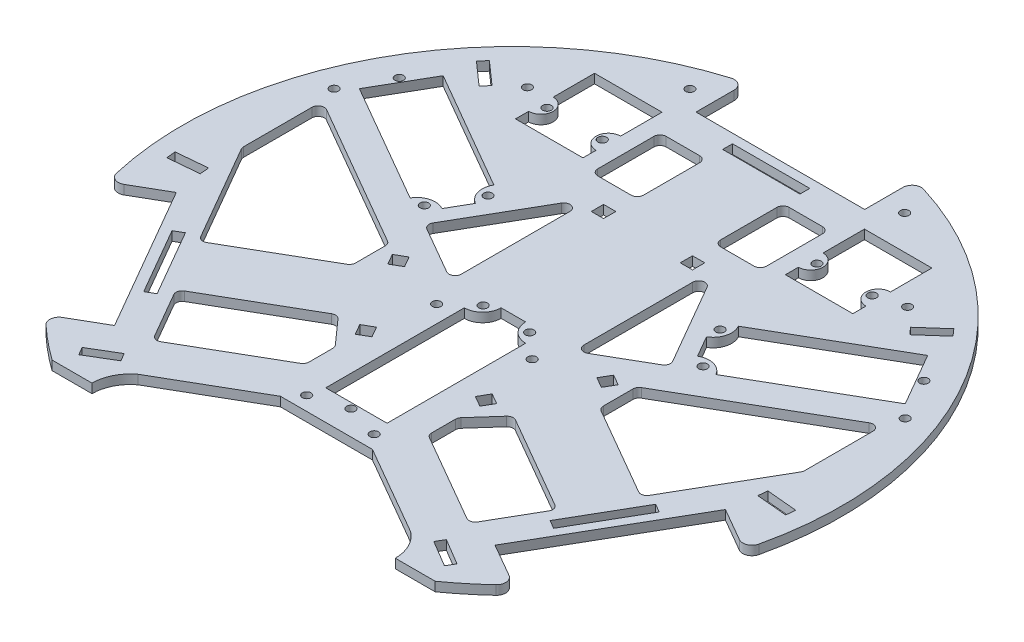
SolidWorks part; units mm, degrees
ref_plane "Front Plane" through (0, 0, 0) normal (0, 0, 1) x (1, 0, 0)
ref_plane "Top Plane" through (0, 0, 0) normal (0, 1, 0) x (1, 0, 0)
ref_plane "Right Plane" through (0, 0, 0) normal (1, 0, 0) x (0, 0, -1)
sketch "Sketch1" plane through (0, 0, 0) normal (0, 1, 0) x (1, 0, 0)
  line L0 (-49.45, -87.5) -> (-62.45, -87.5)
  line L1 (0, -87.5) -> (0, 107.5) construction
  line L2 (12.6, 84.5) -> (12.6, 81.3)
  line L3 (-10, -44.7246) -> (-10, -5.5446)
  line L5 (-15, -60.5) -> (-44.4449, -77.5)
  line L13 (-20.5065, -37.0911) -> (-27.4852, -29.2552)
  line L14 (-29.9787, -28.8533) -> (-60.3868, -46.4078)
  line L15 (-61.119, -49.1398) -> (-52.6196, -63.8626)
  line L17 (-76.6591, -29.8215) -> (-79.4304, -31.4214)
  line L18 (-79.4304, -31.4214) -> (-66.8313, -53.2458)
  line L19 (-66.8313, -53.2458) -> (-64.06, -51.6459)
  line L20 (-64.06, -51.6459) -> (-76.6591, -29.8215)
  line L21 (-12.6, 84.5) -> (0, 84.5)
  line L22 (-71.7662, -73.1838) -> (-62.03, -67.5632)
  line L23 (-62.03, -67.5632) -> (-89.528, -19.9306)
  line L24 (-89.528, -19.9306) -> (-99.2642, -25.5513)
  line L25 (-22.3184, -27.3177) -> (-20.3185, -30.7819)
  line L26 (-20.3185, -30.7819) -> (-16.8543, -28.782)
  line L27 (-16.8543, -28.782) -> (-18.8542, -25.3179)
  line L28 (-18.8542, -25.3179) -> (-22.3184, -27.3177)
  line L29 (-23, 1.7321) -> (-38.342, 10.5897)
  line L30 (-39.074, 13.3218) -> (-23.7321, 39.8949)
  line L31 (-20, 38.8949) -> (-20, 3.4641)
  line L32 (-16.5, 46.359) -> (-16.5, 42.359)
  line L33 (-16.5, 42.359) -> (-12.5, 42.359)
  line L34 (-12.5, 42.359) -> (-12.5, 46.359)
  line L35 (-12.5, 46.359) -> (-16.5, 46.359)
  line L36 (-31.3533, -3.6667) -> (-33.3532, -0.2025)
  line L37 (-33.3532, -0.2025) -> (-36.8174, -2.2024)
  line L38 (-36.8174, -2.2024) -> (-34.8175, -5.6666)
  line L39 (-34.8175, -5.6666) -> (-31.3533, -3.6667)
  line L40 (12.6, 81.3) -> (-12.6, 81.3)
  line L41 (-12.6, 81.3) -> (-12.6, 84.5)
  line L42 (-15, -60.5) -> (15, -60.5)
  line L45 (-40.394, -10.6178) -> (-40.394, -0.9272)
  line L46 (-41.394, 0.8048) -> (-88.47, 27.9842)
  line L47 (-91.47, 26.2521) -> (-91.47, 3.9705)
  line L48 (-91.2021, 2.9706) -> (-73.1181, -28.3547)
  line L49 (-70.3861, -29.0869) -> (-41.3941, -12.3499)
  line L55 (-49.8627, 16.6353) -> (-88.9906, 39.2258)
  line L56 (-88.9906, 39.2258) -> (-78.9906, 56.5463)
  line L57 (-78.9906, 56.5463) -> (-39.8627, 33.9558)
  line L62 (-33, 56.143) -> (-55, 56.143)
  line L64 (-55, 81.923) -> (-33, 81.923)
  line L66 (27.5, 87.5) -> (-27.5, 87.5)
  line L67 (-27.5, 87.5) -> (-27.5, 98.7421)
  line L71 (76.6591, -29.8215) -> (79.4304, -31.4214)
  line L72 (79.4304, -31.4214) -> (66.8313, -53.2458)
  line L73 (66.8313, -53.2458) -> (64.06, -51.6459)
  line L74 (64.06, -51.6459) -> (76.6591, -29.8215)
  line L75 (89.528, -19.9306) -> (99.2642, -25.5513)
  line L76 (62.03, -67.5632) -> (89.528, -19.9306)
  line L77 (71.7662, -73.1838) -> (62.03, -67.5632)
  line L78 (61.119, -49.1398) -> (52.6196, -63.8626)
  line L79 (29.9787, -28.8533) -> (60.3868, -46.4078)
  line L80 (20.5065, -37.0911) -> (27.4852, -29.2552)
  line L83 (22.3184, -27.3177) -> (20.3185, -30.7819)
  line L84 (20.3185, -30.7819) -> (16.8543, -28.782)
  line L85 (16.8543, -28.782) -> (18.8542, -25.3179)
  line L86 (18.8542, -25.3179) -> (22.3184, -27.3177)
  line L87 (33.3532, -0.2025) -> (36.8174, -2.2024)
  line L88 (36.8174, -2.2024) -> (34.8175, -5.6666)
  line L89 (34.8175, -5.6666) -> (31.3533, -3.6667)
  line L90 (31.3533, -3.6667) -> (33.3532, -0.2025)
  line L91 (91.2021, 2.9706) -> (73.1181, -28.3547)
  line L92 (91.47, 26.2521) -> (91.47, 3.9705)
  line L93 (41.394, 0.8048) -> (88.47, 27.9842)
  line L94 (40.394, -10.6178) -> (40.394, -0.9272)
  line L95 (70.3861, -29.0869) -> (41.3941, -12.3499)
  line L96 (20, 38.8949) -> (20, 3.4641)
  line L97 (39.074, 13.3218) -> (23.7321, 39.8949)
  line L98 (23, 1.7321) -> (38.342, 10.5897)
  line L99 (16.5, 46.359) -> (16.5, 42.359)
  line L100 (12.5, 46.359) -> (16.5, 46.359)
  line L101 (12.5, 42.359) -> (12.5, 46.359)
  line L102 (16.5, 42.359) -> (12.5, 42.359)
  line L107 (27.5, 87.5) -> (27.5, 98.7421)
  line L108 (12.6, 84.5) -> (0, 84.5)
  line L109 (10, -44.7246) -> (10, -5.5446)
  line L110 (88.9906, 39.2258) -> (78.9906, 56.5463)
  line L111 (78.9906, 56.5463) -> (39.8627, 33.9558)
  line L112 (49.8627, 16.6353) -> (88.9906, 39.2258)
  line L113 (37.6665, 25.7596) -> (41.6665, 18.8314)
  line L118 (49.45, -87.5) -> (62.45, -87.5)
  line L120 (97.2119, 2.6295) -> (-113.5456, 2.6295) construction
  line L121 (15, -60.5) -> (44.4449, -77.5)
  line L122 (0, -94.5) -> (0, -57.5) construction
  line L123 (-49.8876, -64.5947) -> (-21.0001, -47.9181)
  line L124 (-20, -46.186) -> (-20, -38.4212)
  line L125 (20, -46.186) -> (20, -38.4212)
  line L126 (49.8876, -64.5947) -> (21.0001, -47.9181)
  line L127 (-25.5, 75.7764) -> (-14.6, 75.7764)
  line L128 (-27.5, 73.7764) -> (-27.5, 55.4547)
  line L129 (-12.6, 73.7764) -> (-12.6, 55.4547)
  line L130 (-25.5, 53.4547) -> (-14.6, 53.4547)
  line L131 (27.5, 73.7764) -> (27.5, 55.4547)
  line L132 (25.5, 53.4547) -> (14.6, 53.4547)
  line L133 (12.6, 73.7764) -> (12.6, 55.4547)
  line L134 (25.5, 75.7764) -> (14.6, 75.7764)
  line L135 (27.5, 98.7421) -> (27.5, 99.95)
  line L137 (-27.5, 98.7421) -> (-27.5, 99.95)
  line L139 (-99.2642, -25.5513) -> (-100.3103, -26.1552)
  line L140 (-71.7662, -73.1838) -> (-72.8123, -73.7877)
  line L141 (99.2642, -25.5513) -> (100.3103, -26.1552)
  line L143 (71.7662, -73.1838) -> (72.8123, -73.7877)
  line L144 (-37.6665, 25.7596) -> (-41.6665, 18.8314)
  line L145 (-4, -50.7246) -> (4, -50.7246)
  line L154 (-33, 81.923) -> (-33, 68.408)
  line L155 (-55, 81.923) -> (-55, 68.423)
  line L156 (-55, 60.423) -> (-55, 56.143)
  line L157 (-33, 60.408) -> (-33, 56.143)
  line L158 (33, 81.923) -> (33, 68.408)
  line L159 (33, 60.408) -> (33, 56.143)
  line L160 (33, 56.143) -> (55, 56.143)
  line L161 (55, 60.423) -> (55, 56.143)
  line L162 (55, 81.923) -> (55, 68.423)
  line L163 (55, 81.923) -> (33, 81.923)
  line L164 (-4, 0.4554) -> (4, 0.4554)
  line L165 (4, -50.7246) -> (10, -50.7246)
  line L166 (10, -50.7246) -> (10, -44.7246)
  line L167 (-10, -44.7246) -> (-10, -50.7246)
  line L168 (-10, -50.7246) -> (-4, -50.7246)
  circle A6 centre (0, -94.5) radius 37 construction
  arc A7 (-62.45, -87.5) -> (-73.3596, -78.5787) centre (0, 0) cw
  circle A20 centre (-62, 67) radius 1.4
  circle A24 centre (-15.5888, -8.9994) radius 1.4
  arc A27 (-49.45, -87.5) -> (-44.4449, -77.5) centre (-36.9576, -87.5) cw
  arc A28 (49.45, -87.5) -> (44.4449, -77.5) centre (36.9576, -87.5) ccw
  arc A29 (31.3756, 102.8194) -> (104.733, -24.2333) centre (0, 0) cw
  arc A30 (73.3596, -78.5787) -> (62.45, -87.5) centre (0, 0) cw
  arc A31 (-104.733, -24.2333) -> (-31.3756, 102.8194) centre (0, 0) cw
  circle A38 centre (15.5888, -8.9994) radius 1.4
  circle A42 centre (62, 67) radius 1.4
  circle A44 centre (85.5304, 48.775) radius 1.4
  circle A46 centre (45.4411, 16.8537) radius 1.4
  circle A47 centre (37.8411, 30.0173) radius 1.4
  arc A48 (41.6665, 18.8314) -> (49.8627, 16.6353) centre (44.6665, 13.6353) cw
  arc A49 (39.8627, 33.9558) -> (37.6665, 25.7596) centre (34.6665, 30.9558) cw
  circle A50 centre (-37.8411, 30.0173) radius 1.4
  arc A51 (-39.8627, 33.9558) -> (-37.6665, 25.7596) centre (-34.6665, 30.9558) ccw
  arc A52 (-41.6665, 18.8314) -> (-49.8627, 16.6353) centre (-44.6665, 13.6353) ccw
  circle A53 centre (-45.4411, 16.8537) radius 1.4
  circle A54 centre (-85.5304, 48.775) radius 1.4
  circle A59 centre (-53, 64.423) radius 1.4
  circle A60 centre (-35, 64.423) radius 1.4
  arc A67 (-33, 68.408) -> (-33, 60.408) centre (-33, 64.408) ccw
  arc A68 (-55, 68.423) -> (-55, 60.423) centre (-55, 64.423) cw
  arc A69 (33, 68.408) -> (33, 60.408) centre (33, 64.408) cw
  circle A70 centre (35, 64.423) radius 1.4
  circle A71 centre (53, 64.423) radius 1.4
  arc A72 (55, 68.423) -> (55, 60.423) centre (55, 64.423) ccw
  arc A73 (27.5, 99.95) -> (31.3756, 102.8194) centre (30.5, 99.95) cw
  arc A74 (104.733, -24.2333) -> (100.3103, -26.1552) centre (101.8102, -23.557) cw
  arc A75 (72.8123, -73.7877) -> (73.3596, -78.5787) centre (71.3124, -76.3858) cw
  arc A76 (-73.3596, -78.5787) -> (-72.8123, -73.7877) centre (-71.3124, -76.3858) cw
  arc A77 (-104.733, -24.2333) -> (-100.3103, -26.1552) centre (-101.8102, -23.557) ccw
  arc A78 (-31.3756, 102.8194) -> (-27.5, 99.95) centre (-30.5, 99.95) cw
  circle A79 centre (7.6, -1.8246) radius 1.4
  circle A80 centre (-7.6, -1.8246) radius 1.4
  arc A81 (4, 0.4554) -> (10, -5.5446) centre (10, 0.4554) ccw
  arc A82 (-4, 0.4554) -> (-10, -5.5446) centre (-10, 0.4554) cw
  circle A83 centre (0, -52.5026) radius 1.4
  arc A84 (-23.7321, 39.8949) -> (-20, 38.8949) centre (-22, 38.8949) cw
  arc A85 (-20, 3.4641) -> (-23, 1.7321) centre (-22, 3.4641) cw
  arc A86 (-39.074, 13.3218) -> (-38.342, 10.5897) centre (-37.342, 12.3218) ccw
  arc A87 (27.4852, -29.2552) -> (29.9787, -28.8533) centre (28.9787, -30.5854) cw
  arc A88 (60.3868, -46.4078) -> (61.119, -49.1398) centre (59.3869, -48.1399) cw
  arc A89 (52.6196, -63.8626) -> (49.8876, -64.5947) centre (50.8875, -62.8627) cw
  arc A90 (21.0001, -47.9181) -> (20, -46.186) centre (22, -46.186) cw
  arc A91 (20, -38.4212) -> (20.5065, -37.0911) centre (22, -38.4212) cw
  arc A92 (-21.0001, -47.9181) -> (-20, -46.186) centre (-22, -46.186) ccw
  arc A93 (-20, -38.4212) -> (-20.5065, -37.0911) centre (-22, -38.4212) ccw
  arc A94 (-29.9787, -28.8533) -> (-27.4852, -29.2552) centre (-28.9787, -30.5854) cw
  arc A95 (-61.119, -49.1398) -> (-60.3868, -46.4078) centre (-59.3869, -48.1399) cw
  arc A96 (-52.6196, -63.8626) -> (-49.8876, -64.5947) centre (-50.8875, -62.8627) ccw
  arc A97 (88.47, 27.9842) -> (91.47, 26.2521) centre (89.47, 26.2521) cw
  arc A98 (91.2021, 2.9706) -> (91.47, 3.9705) centre (89.47, 3.9705) ccw
  arc A99 (70.3861, -29.0869) -> (73.1181, -28.3547) centre (71.386, -27.3548) ccw
  arc A100 (41.3941, -12.3499) -> (40.394, -10.6178) centre (42.394, -10.6178) cw
  arc A101 (40.394, -0.9272) -> (41.394, 0.8048) centre (42.394, -0.9272) cw
  arc A102 (-41.394, 0.8048) -> (-40.394, -0.9272) centre (-42.394, -0.9272) cw
  arc A103 (-41.3941, -12.3499) -> (-40.394, -10.6178) centre (-42.394, -10.6178) ccw
  arc A104 (-70.3861, -29.0869) -> (-73.1181, -28.3547) centre (-71.386, -27.3548) cw
  arc A105 (-91.2021, 2.9706) -> (-91.47, 3.9705) centre (-89.47, 3.9705) cw
  arc A106 (-91.47, 26.2521) -> (-88.47, 27.9842) centre (-89.47, 26.2521) cw
  arc A107 (-14.6, 75.7764) -> (-12.6, 73.7764) centre (-14.6, 73.7764) cw
  arc A108 (-14.6, 53.4547) -> (-12.6, 55.4547) centre (-14.6, 55.4547) ccw
  arc A109 (-25.5, 53.4547) -> (-27.5, 55.4547) centre (-25.5, 55.4547) cw
  arc A110 (-27.5, 73.7764) -> (-25.5, 75.7764) centre (-25.5, 73.7764) cw
  arc A111 (25.5, 53.4547) -> (27.5, 55.4547) centre (25.5, 55.4547) ccw
  arc A112 (14.6, 53.4547) -> (12.6, 55.4547) centre (14.6, 55.4547) cw
  arc A113 (12.6, 73.7764) -> (14.6, 75.7764) centre (14.6, 73.7764) cw
  arc A114 (27.5, 73.7764) -> (25.5, 75.7764) centre (25.5, 73.7764) ccw
  arc A115 (38.342, 10.5897) -> (39.074, 13.3218) centre (37.342, 12.3218) ccw
  arc A116 (23, 1.7321) -> (20, 3.4641) centre (22, 3.4641) cw
  arc A117 (20, 38.8949) -> (23.7321, 39.8949) centre (22, 38.8949) cw
  point P8 (0, -60.5)
  point P93 (0, 87.5)
  point P130 (27.5, 103.923)
  point P134 (103.7512, -28.1416)
  point P141 (76.2531, -75.7741)
  point P146 (-103.7512, -28.1416)
  point P151 (0, 0.68)
  point P155 (-20, 46.359)
  point P156 (0, -50.5)
  point P165 (-20, 0)
  point P168 (-40.074, 11.5897)
  point P171 (28.5683, -28.0391)
  point P175 (62.1189, -47.4077)
  point P181 (51.6197, -65.5947)
  point P185 (20, -47.3408)
  point P188 (20, -37.6597)
  point P194 (-20, -47.3408)
  point P197 (-20, -37.6597)
  point P200 (-28.5683, -28.0391)
  point P203 (-62.1189, -47.4077)
  point P206 (-51.6197, -65.5947)
  point P209 (91.47, 29.7162)
  point P221 (91.47, 3.4347)
  point P225 (72.1182, -30.0868)
  point P229 (40.394, -11.7725)
  point P243 (40.394, 0.2275)
  point P249 (-40.394, 0.2275)
  point P254 (-40.394, -11.7725)
  point P257 (-72.1182, -30.0868)
  point P267 (-91.47, 3.4347)
  point P272 (0, 81.3)
  point P273 (-91.47, 29.7162)
  point P279 (-12.6, 75.7764)
  point P285 (-12.6, 53.4547)
  point P287 (0, -52.5026)
  point P289 (-27.5, 53.4547)
  point P292 (-27.5, 75.7764)
  point P295 (27.5, 53.4547)
  point P298 (12.6, 53.4547)
  point P301 (12.6, 75.7764)
  point P304 (27.5, 75.7764)
  point P307 (40.074, 11.5897)
  point P310 (20, 0)
  point P313 (20, 46.359)
  dimension "D1" = 107.5
  dimension "D4" = 91.2853
  dimension "D6" = 30
  dimension "D10" = 34
  dimension "D5" = 150
  dimension "D7" = 27
  dimension "D8" = 74
  dimension "D9" = 30
  dimension "D12" = 2
  dimension "D14" = 13
  dimension "D15" = 180
  dimension "D16" = 8
  dimension "D17" = 8
  dimension "D18" = 150
  dimension "D19" = 98.9
  dimension "D20" = 22
  dimension "D21" = 3
  dimension "D22" = 3
  dimension "D25" = 2.8
  dimension "D26" = 1.778
  dimension "D27" = 2.8
  dimension "D28" = 2.8
  dimension "D29" = 2.28
  dimension "D30" = 2.28
  dimension "D31" = 2.4
  dimension "D33" = 20
  dimension "D34" = 20
  dimension "D35" = 6
  dimension "D36" = 6
  dimension "D39" = 2
  dimension "D40" = 10
  dimension "D41" = 2.8
  dimension "D42" = 2.8
  dimension "D43" = 3.2
  dimension "D44" = 3
  dimension "D45" = 25.2
  dimension "D46" = 25.2
  dimension "D13" = 2.8
  dimension "D37" = 2.8
  dimension "D47" = 17.5
  dimension "D48" = 17.5
  dimension "D49" = 2.4
  dimension "D50" = 2.4
  dimension "D51" = 3.2
  dimension "D52" = 3
  dimension "D53" = 15.2
  dimension "D54" = 3.3103
  dimension "D55" = 6
  dimension "D62" = 18
  dimension "D64" = 2
  dimension "D65" = 51.2457
  dimension "D66" = 2.8
  dimension "D67" = 50.678
  dimension "D11" = 62
  dimension "D23" = 51.181
  dimension "D24" = 5
  dimension "D32" = 2.4
  dimension "D38" = 1.778
  dimension "D56" = 52.959
  dimension "D57" = 20
  dimension "D58" = 22
  dimension "D59" = 13.5
  dimension "D60" = 4.28
  dimension "D61" = 25.78
  dimension "D63" = 2
sketch "Sketch2" plane through (0, 0, 0) normal (0, 1, 0) x (1, 0, 0)
  line L0 (0, -200087.5) -> (0, 200107.5) construction
  line L3 (0, 107.5) -> (0, -87.5) construction
  circle A0 centre (-35, 93.0342) radius 1.4
  circle A1 centre (-93.1034, 35.1) radius 1.4
  circle A2 centre (-11, -55.9285) radius 1.4
  circle A3 centre (11, -55.9285) radius 1.4
  circle A4 centre (93.1034, 35.1) radius 1.4
  circle A5 centre (35, 93.0342) radius 1.4
  circle A6 centre (-58, -78.9937) radius 1.4
  circle A7 centre (58, -78.9937) radius 1.4
  circle A8 centre (0, 0) radius 107.5
  arc A9 (-73.3596, -78.5787) -> (-62.45, -87.5) centre (0, 0) ccw construction
  dimension "D1" = 2.8
  dimension "D4" = 2.8
  dimension "D5" = 35.1
  dimension "D6" = 99.5
  dimension "D7" = 2.8
  dimension "D8" = 57
  dimension "D9" = 11
  dimension "D10" = 2.8
  dimension "D12" = 99.4
  dimension "D11" = 35
  dimension "D13" = 93.1034
  dimension "D17" = 58
  dimension "D18" = 98
  dimension "D19" = 70
  dimension "D22" = 22
  dimension "D3" = 35
extrude "Base" add sketch "Sketch1" along normal blind 3
sketch "Sketch5" plane through (0, 3, 0) normal (0, 1, 0) x (1, 0, 0)
  line L8 (0, 137.4812) -> (0, -98.0674) construction
  line L9 (-61.1276, -79.0484) -> (-52.5405, -73.9239)
  line L10 (-52.5405, -73.9239) -> (-51.0031, -76.5)
  line L11 (90.9, -10.7432) -> (91.1724, -7.7556)
  line L12 (101.1724, -8.6674) -> (91.1724, -7.7556)
  line L13 (100.9, -11.655) -> (90.9, -10.7432)
  line L14 (100.9, -11.655) -> (101.1724, -8.6674)
  line L15 (70.2156, 59.4796) -> (68.2269, 61.7257)
  line L16 (75.7142, 68.3546) -> (68.2269, 61.7257)
  line L17 (77.7028, 66.1084) -> (70.2156, 59.4796)
  line L18 (77.7028, 66.1084) -> (75.7142, 68.3546)
  line L19 (-100.9, -11.655) -> (-101.1724, -8.6674)
  line L20 (-100.9, -11.655) -> (-90.9, -10.7432)
  line L21 (-101.1724, -8.6674) -> (-91.1724, -7.7556)
  line L22 (-90.9, -10.7432) -> (-91.1724, -7.7556)
  line L23 (-77.7028, 66.1084) -> (-75.7142, 68.3546)
  line L24 (-75.7142, 68.3546) -> (-68.2269, 61.7257)
  line L25 (-77.7028, 66.1084) -> (-70.2156, 59.4796)
  line L26 (-70.2156, 59.4796) -> (-68.2269, 61.7257)
  line L27 (-51.0031, -76.5) -> (-59.5902, -81.6246)
  line L28 (-59.5902, -81.6246) -> (-61.1276, -79.0484)
  line L29 (-62.45, -87.5) -> (-49.45, -87.5) construction
  line L30 (52.5405, -73.9239) -> (51.0031, -76.5)
  line L31 (51.0031, -76.5) -> (59.5902, -81.6246)
  line L32 (59.5902, -81.6246) -> (61.1276, -79.0484)
  line L33 (61.1276, -79.0484) -> (52.5405, -73.9239)
  circle A0 centre (0, 0) radius 107.5
  circle A1 centre (0, 0) radius 107.5 construction
  dimension "D6" = 10
  dimension "D1" = 92
  dimension "D2" = 75.7142
  dimension "D3" = 91.5
  dimension "D4" = 10
  dimension "D5" = 91.1724
  dimension "D7" = 10
  dimension "D8" = 3
  dimension "D9" = 3
  dimension "D10" = 10
  dimension "D11" = 3
  dimension "D12" = 3
  dimension "D13" = 68.2269
  dimension "D14" = 101.1724
  dimension "D15" = 77.7028
  dimension "D16" = 100.9
  dimension "D17" = 3
  dimension "D18" = 10
  dimension "D19" = 3
  dimension "D20" = 93
  dimension "D21" = 11
extrude "Holes de soports" cut sketch "Sketch2" along normal blind 3 contours A3 | A0 | A1 | A2 | A7 | A4 | A5 | A6
extrude "Cut de soportes" cut sketch "Sketch5" against normal blind 3 contours L28 L27 L10 L9 | L24 L26 L25 L23 | L21 L22 L20 L19 | L13 L11 L12 L14 | L17 L15 L16 L18 | L33 L30 L31 L32
